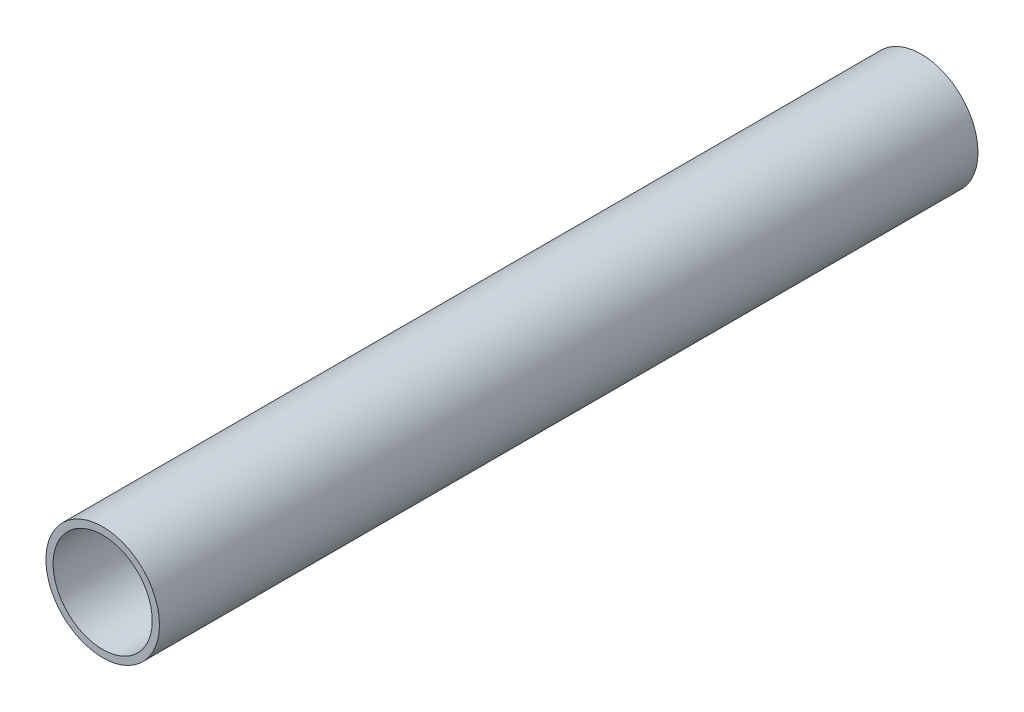
SolidWorks part; units mm, degrees
ref_plane "Front Plane" through (0, 0, 0) normal (0, 0, 1) x (1, 0, 0)
ref_plane "Top Plane" through (0, 0, 0) normal (0, 1, 0) x (1, 0, 0)
ref_plane "Right Plane" through (0, 0, 0) normal (1, 0, 0) x (0, 0, -1)
sketch "Sketch1" plane through (0, 0, 0) normal (0, 0, 1) x (1, 0, 0)
  circle A0 centre (0, 0) radius 9.017
  circle A1 centre (0, 0) radius 7.874
extrude "Boss-Extrude1" add sketch "Sketch1" along normal blind 130
